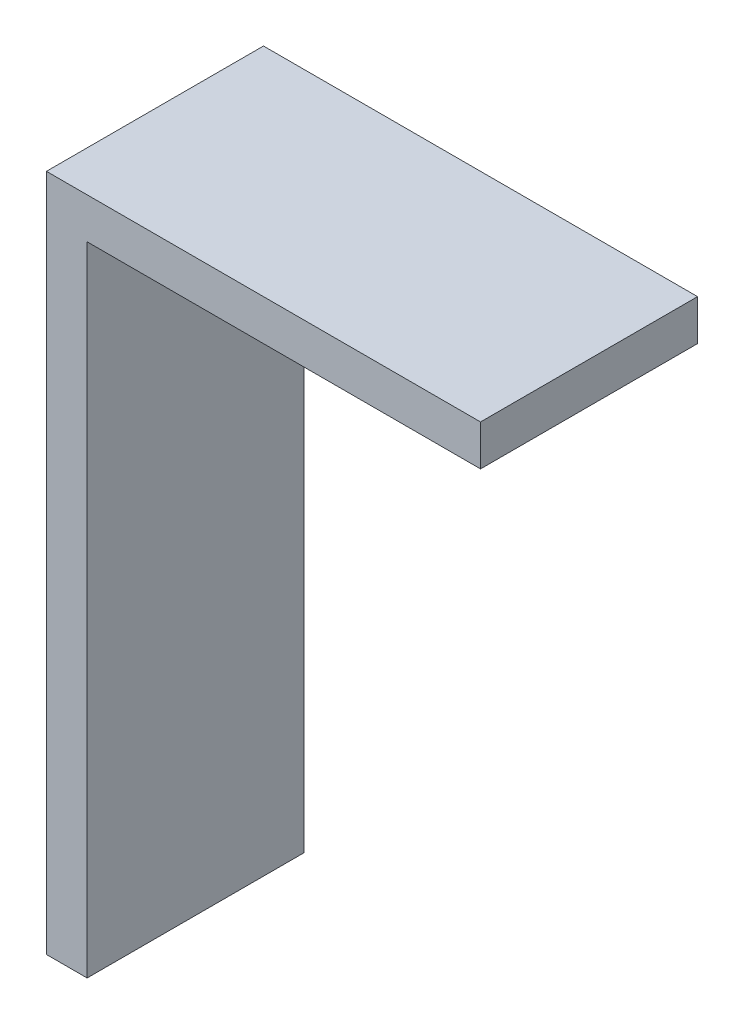
SolidWorks part; units mm, degrees
ref_plane "Alzado" through (0, 0, 0) normal (0, 0, 1) x (1, 0, 0)
ref_plane "Planta" through (0, 0, 0) normal (0, 1, 0) x (1, 0, 0)
ref_plane "Vista lateral" through (0, 0, 0) normal (1, 0, 0) x (0, 0, -1)
sketch "Croquis1" plane through (0, 0, 0) normal (0, 0, 1) x (1, 0, 0)
  line L0 (0, 0) -> (0, 500)
  line L1 (0, 500) -> (320, 500)
  line L2 (30, 0) -> (30, 470)
  line L3 (30, 470) -> (320, 470)
  line L4 (0, 0) -> (30, 0)
  line L5 (320, 500) -> (320, 470)
  dimension "D1" = 500
  dimension "D2" = 320
  dimension "D3" = 30
extrude "Saliente-Extruir1" add sketch "Croquis1" along normal blind 160
